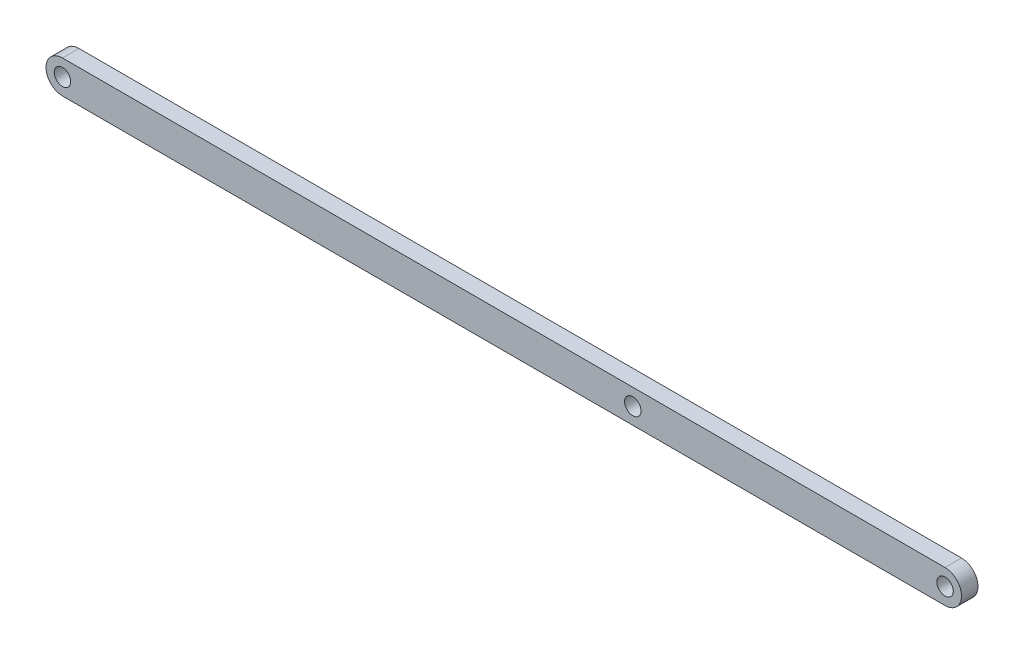
SolidWorks part; units mm, degrees
ref_plane "Plano frontal" through (0, 0, 0) normal (0, 0, 1) x (1, 0, 0)
ref_plane "Plano superior" through (0, 0, 0) normal (0, 1, 0) x (1, 0, 0)
ref_plane "Plano direito" through (0, 0, 0) normal (1, 0, 0) x (0, 0, -1)
sketch "Esboço1" plane through (0, 0, 0) normal (0, 0, 1) x (1, 0, 0)
  line L0 (-227.28, 5) -> (40.72, 5)
  line L2 (-227.28, -5) -> (40.72, -5)
  arc A0 (-227.28, 5) -> (-227.28, -5) centre (-227.28, 0) ccw
  arc A1 (40.72, 5) -> (40.72, -5) centre (40.72, 0) cw
  circle A2 centre (-227.28, 0) radius 2.5
  circle A3 centre (40.72, 0) radius 2.5
  circle A4 centre (-54.1, 0) radius 2.5
  point P3 (-93.28, 5)
  dimension "D1" = 268
extrude "Ressalto-extrusão1" add sketch "Esboço1" along normal blind 5
